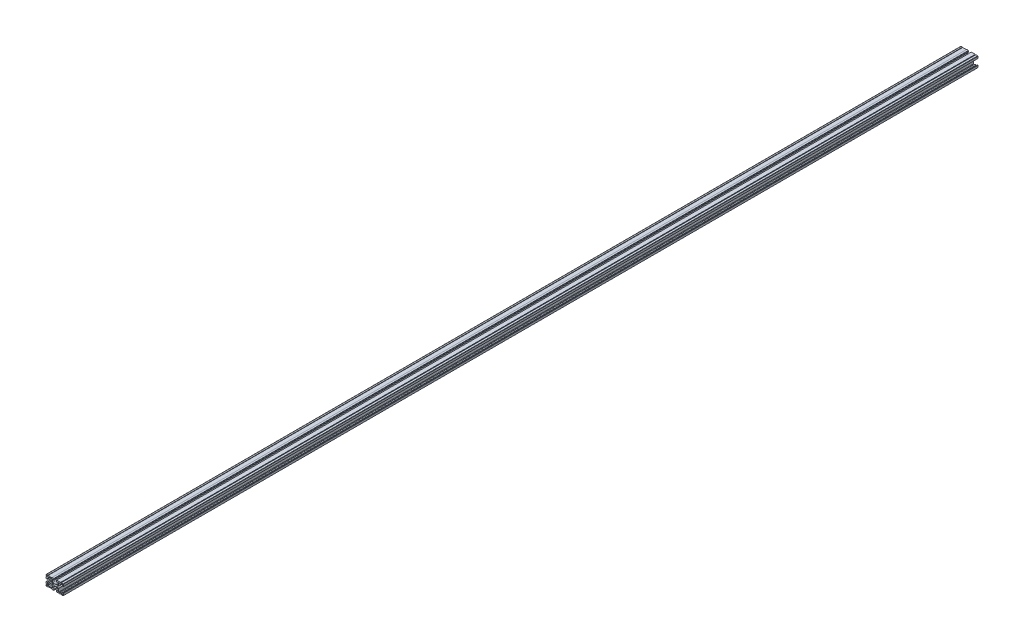
SolidWorks part; units mm, degrees
ref_plane "Front Plane" through (0, 0, 0) normal (0, 0, 1) x (1, 0, 0)
ref_plane "Top Plane" through (0, 0, 0) normal (0, 1, 0) x (1, 0, 0)
ref_plane "Right Plane" through (0, 0, 0) normal (1, 0, 0) x (0, 0, -1)
sketch "Sketch1" plane through (0, 0, 0) normal (0, 0, 1) x (1, 0, 0)
  line L0 (-8.0424, 6.5202) -> (-2.1718, 4.3835)
  line L1 (8.0424, 6.5202) -> (2.1718, 4.3835)
  line L2 (-8.0424, -6.5202) -> (-2.1718, -4.3835)
  line L3 (8.0424, -6.5202) -> (2.1718, -4.3835)
  line L4 (-6.0452, 20.6756) -> (-6.0452, 22.352)
  line L5 (-5.207, 20.6756) -> (-6.0452, 20.6756)
  line L6 (6.0452, 20.6756) -> (5.207, 20.6756)
  line L7 (-5.207, 16.383) -> (-5.207, 20.6756)
  line L8 (5.207, 16.383) -> (5.207, 20.6756)
  line L9 (-13.8176, 20.828) -> (-13.8176, 22.352)
  line L10 (-13.8176, 20.828) -> (-31.4452, 20.828)
  line L11 (-6.0452, 22.352) -> (-13.8176, 22.352)
  line L12 (-31.4452, 20.828) -> (-31.4452, 22.352)
  line L13 (6.0452, 20.6756) -> (6.0452, 22.352)
  line L14 (-29.083, 10.9982) -> (-29.083, 13.843)
  line L15 (-14.986, 4.449) -> (-14.986, 17.018)
  line L16 (-14.986, 17.018) -> (-25.908, 17.018)
  line L17 (-11.176, 10.9954) -> (-11.176, 16.383)
  line L18 (-5.207, 16.383) -> (-11.176, 16.383)
  line L19 (11.176, 10.9954) -> (11.176, 16.383)
  line L20 (11.176, 16.383) -> (5.207, 16.383)
  line L21 (-5.207, -16.383) -> (-11.176, -16.383)
  line L22 (11.176, -16.383) -> (5.207, -16.383)
  line L23 (6.0452, -20.6756) -> (5.207, -20.6756)
  line L24 (-5.207, -20.6756) -> (-6.0452, -20.6756)
  line L25 (-5.207, -20.6756) -> (-5.207, -16.383)
  line L26 (5.207, -20.6756) -> (5.207, -16.383)
  line L27 (6.0452, -22.352) -> (6.0452, -20.6756)
  line L28 (-6.0452, -22.352) -> (-6.0452, -20.6756)
  line L29 (11.176, -16.383) -> (11.176, -10.9954)
  line L30 (-11.176, -16.383) -> (-11.176, -10.9954)
  line L31 (-29.083, 10.9982) -> (-34.163, 10.9982)
  line L32 (-34.163, 5.0165) -> (-34.163, 10.9982)
  line L33 (-40.132, 5.9055) -> (-38.481, 5.9055)
  line L34 (-38.481, 5.0165) -> (-34.163, 5.0165)
  line L35 (-38.481, 5.0165) -> (-38.481, 5.9055)
  line L36 (-38.227, 12.9667) -> (-36.134, 15.0597)
  line L37 (-13.8176, -20.828) -> (-31.4452, -20.828)
  line L38 (-31.4452, -20.828) -> (-31.4452, -22.352)
  line L39 (-29.083, -10.9982) -> (-29.083, -13.843)
  line L40 (-29.083, -10.9982) -> (-34.163, -10.9982)
  line L41 (-34.163, -5.0165) -> (-34.163, -10.9982)
  line L42 (-38.481, -5.0165) -> (-34.163, -5.0165)
  line L43 (-38.481, -5.0165) -> (-38.481, -5.9055)
  line L44 (-38.227, -12.9667) -> (-36.134, -15.0597)
  line L45 (-40.132, -5.9055) -> (-38.481, -5.9055)
  line L46 (-13.8176, -20.828) -> (-13.8176, -22.352)
  line L47 (-6.0452, -22.352) -> (-13.8176, -22.352)
  line L48 (-14.986, -17.018) -> (-25.908, -17.018)
  line L49 (-14.986, -17.018) -> (-14.986, -4.449)
  line L50 (-40.132, 12.9667) -> (-38.227, 12.9667)
  line L51 (-40.132, 5.9055) -> (-40.132, 12.9667)
  line L52 (-40.132, -12.9667) -> (-40.132, -5.9055)
  line L53 (-40.132, -12.9667) -> (-38.227, -12.9667)
  line L54 (-40.132, 17.4879) -> (-40.132, 19.177)
  line L55 (-31.4452, 22.352) -> (-36.957, 22.352)
  line L56 (-38.227, 17.4879) -> (-40.132, 17.4879)
  line L57 (-37.5141, 18.7534) -> (-38.227, 17.4879)
  line L58 (-37.5141, -18.7534) -> (-38.227, -17.4879)
  line L59 (-38.227, -17.4879) -> (-40.132, -17.4879)
  line L60 (-40.132, -19.177) -> (-40.132, -17.4879)
  line L61 (-31.4452, -22.352) -> (-36.957, -22.352)
  line L62 (34.163, 21.082) -> (34.163, 22.352)
  line L63 (35.052, 21.082) -> (34.163, 21.082)
  line L64 (23.114, 19.685) -> (23.114, 22.352)
  line L65 (26.162, 19.685) -> (26.162, 22.352)
  line L66 (26.162, 19.685) -> (23.114, 19.685)
  line L67 (34.163, 22.352) -> (26.162, 22.352)
  line L68 (23.114, 22.352) -> (6.0452, 22.352)
  line L69 (14.986, 4.449) -> (14.986, 18.0848)
  line L70 (33.147, 12.6365) -> (32.2997, 16.4586)
  line L71 (27.432, 15.5194) -> (23.114, 15.5194)
  line L72 (16.7513, 18.0848) -> (14.986, 18.0848)
  line L73 (27.432, 15.5194) -> (27.432, 17.4752)
  line L74 (34.163, -21.082) -> (34.163, -22.352)
  line L75 (23.114, -19.685) -> (23.114, -22.352)
  line L76 (26.162, -19.685) -> (26.162, -22.352)
  line L77 (26.162, -19.685) -> (23.114, -19.685)
  line L78 (35.052, -12.6365) -> (33.147, -12.6365)
  line L79 (33.147, -12.6365) -> (32.2997, -16.4586)
  line L80 (27.432, -15.5194) -> (23.114, -15.5194)
  line L81 (27.432, -15.5194) -> (27.432, -17.4752)
  line L82 (16.7513, -18.0848) -> (14.986, -18.0848)
  line L83 (14.986, -18.0848) -> (14.986, -4.449)
  line L84 (23.114, -22.352) -> (6.0452, -22.352)
  line L85 (34.163, -22.352) -> (26.162, -22.352)
  line L86 (2.1718, 4.3835) -> (-2.1718, -4.3835) construction
  line L87 (35.052, -21.082) -> (35.052, -12.6365)
  line L88 (35.052, -21.082) -> (34.163, -21.082)
  line L89 (35.052, 12.6365) -> (35.052, 21.082)
  line L90 (35.052, 12.6365) -> (33.147, 12.6365)
  arc A0 (-14.986, 4.449) -> (-14.1125, 3.8605) centre (-14.351, 4.449) ccw
  arc A1 (-14.1125, -3.8605) -> (-14.1125, 3.8605) centre (-12.5476, 0) ccw
  arc A2 (14.1125, 3.8605) -> (14.1125, -3.8605) centre (12.5476, 0) ccw
  arc A3 (14.1125, 3.8605) -> (14.986, 4.449) centre (14.351, 4.449) ccw
  arc A4 (-11.176, 10.9954) -> (-8.0424, 6.5202) centre (-6.4135, 10.9954) ccw
  arc A5 (8.0424, 6.5202) -> (11.176, 10.9954) centre (6.4135, 10.9954) ccw
  arc A6 (-2.1718, 4.3835) -> (2.1718, 4.3835) centre (0, 10.3505) ccw
  arc A7 (2.1718, -4.3835) -> (-2.1718, -4.3835) centre (0, -10.3505) ccw
  arc A8 (-25.908, 17.018) -> (-29.083, 13.843) centre (-25.908, 13.843) ccw
  arc A9 (-14.1125, -3.8605) -> (-14.986, -4.449) centre (-14.351, -4.449) ccw
  arc A10 (14.986, -4.449) -> (14.1125, -3.8605) centre (14.351, -4.449) ccw
  arc A11 (11.176, -10.9954) -> (8.0424, -6.5202) centre (6.4135, -10.9954) ccw
  arc A12 (-8.0424, -6.5202) -> (-11.176, -10.9954) centre (-6.4135, -10.9954) ccw
  arc A13 (-29.083, -13.843) -> (-25.908, -17.018) centre (-25.908, -13.843) ccw
  arc A14 (-36.957, 22.352) -> (-40.132, 19.177) centre (-36.957, 19.177) ccw
  arc A15 (-36.134, 15.0597) -> (-37.5141, 18.7534) centre (-35.2679, 17.4879) ccw
  arc A16 (-37.5141, -18.7534) -> (-36.134, -15.0597) centre (-35.2679, -17.4879) ccw
  arc A17 (-40.132, -19.177) -> (-36.957, -22.352) centre (-36.957, -19.177) ccw
  arc A18 (32.2997, 16.4586) -> (27.432, 17.4752) centre (29.972, 17.4752) ccw
  arc A19 (19.4368, 17.2554) -> (23.114, 15.5194) centre (23.114, 20.2819) ccw
  arc A20 (19.4368, 17.2554) -> (16.7513, 18.0848) centre (16.7513, 13.3223) ccw
  arc A21 (27.432, -17.4752) -> (32.2997, -16.4586) centre (29.972, -17.4752) ccw
  arc A22 (23.114, -15.5194) -> (19.4368, -17.2554) centre (23.114, -20.2819) ccw
  arc A23 (16.7513, -18.0848) -> (19.4368, -17.2554) centre (16.7513, -13.3223) ccw
  point P0 (0, 0)
extrude "Extrude1" add sketch "Sketch1" along normal blind 3962.4
